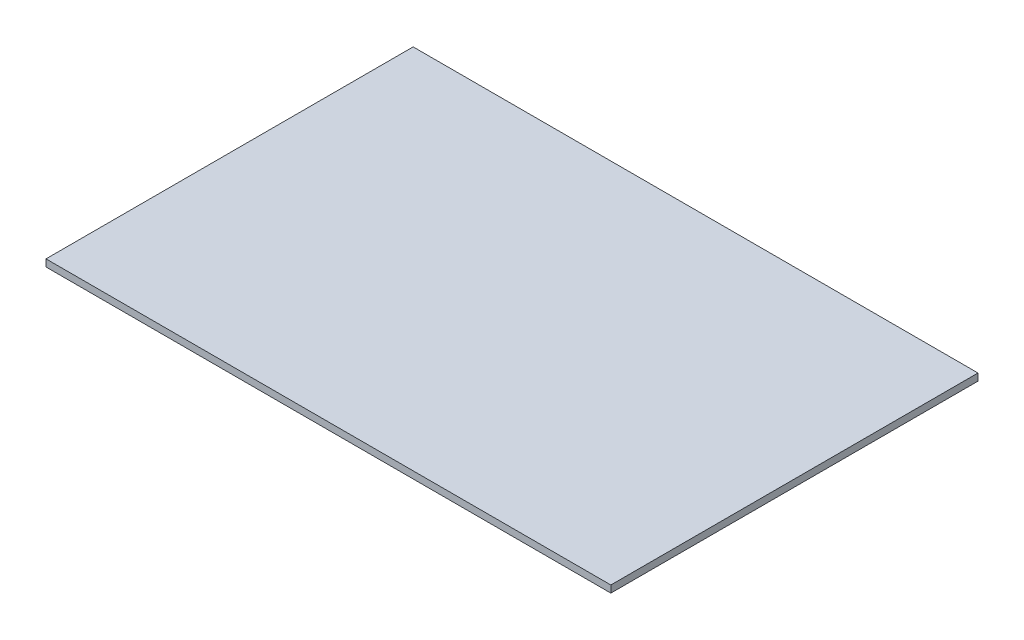
SolidWorks part; units mm, degrees
material "PVC 0.007 Plasticized"
ref_plane "Front Plane" through (0, 0, 0) normal (0, 0, 1) x (1, 0, 0)
ref_plane "Top Plane" through (0, 0, 0) normal (0, 1, 0) x (1, 0, 0)
ref_plane "Right Plane" through (0, 0, 0) normal (1, 0, 0) x (0, 0, -1)
sketch "Sketch1" plane through (0, 0, 0) normal (0, 1, 0) x (1, 0, 0)
  line L1 (0, 0) -> (120, 0)
  line L2 (0, 0) -> (0, 78)
  line L3 (0, 78) -> (120, 78)
  line L4 (120, 0) -> (120, 78)
  dimension "D1" = 120
  dimension "D2" = 78
extrude "Boss-Extrude1" add sketch "Sketch1" along normal blind 1.5
